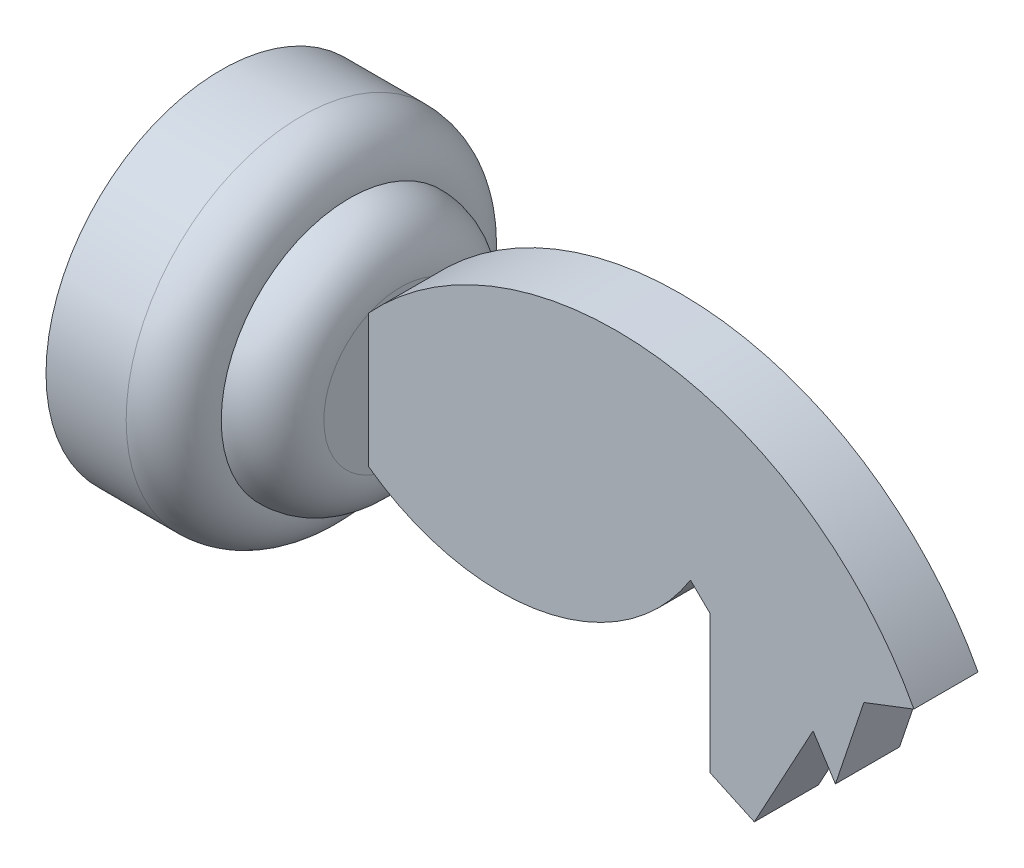
SolidWorks part; units mm, degrees
ref_plane "Спереди" through (0, 0, 0) normal (0, 0, 1) x (1, 0, 0)
ref_plane "Сверху" through (0, 0, 0) normal (0, 1, 0) x (1, 0, 0)
ref_plane "Справа" through (0, 0, 0) normal (1, 0, 0) x (0, 0, -1)
other "Configuration Table"
sketch "Эскиз1" plane through (0, 0, 0) normal (0, 0, 1) x (1, 0, 0)
  line L0 (0, 0) -> (71.2267, 0) construction
sketch "попа" plane through (0, 0, 0) normal (0, 0, 1) x (1, 0, 0)
  line L0 (0, 0) -> (0, 10.9299)
  line L1 (0, 10.9299) -> (5, 10.9299)
  line L3 (0, 0) -> (71.2267, 0) construction
  line L7 (11.2, 4.8) -> (11.2, 0)
  line L8 (11.2, 0) -> (0, 0)
  line L9 (8, 0) -> (8, 8)
  line L10 (11.2, 2.4) -> (11.2, 0)
  line L11 (0, 0) -> (-9.6864, 0) construction
  line L16 (1, 0) -> (3.5, 0)
  line L17 (1, 0) -> (1, 5.25)
  line L18 (1, 5.25) -> (3.5, 5.25)
  line L19 (3.5, 5.25) -> (3.5, 0)
  arc A0 (8, 8) -> (5, 10.9299) centre (5.0008, 7.9299) ccw
  arc A1 (11.2, 4.8) -> (8, 8) centre (8, 4.8) ccw
  dimension "D6" = 3
  dimension "D7" = 3.2
  dimension "D9" = 5.25
  dimension "D10" = 2.5
  dimension "D1" = 8
  dimension "D2" = 5
  dimension "D3" = 11.2
  dimension "D4" = 4.8
  dimension "D5" = 8
  dimension "D8" = 1
  dimension "D11" = 2.9992
revolve "Повернуть1" add sketch "попа" angle 360 about L0
sketch "вверх" plane through (0, 0, 0) normal (0, 0, 1) x (1, 0, 0)
  line L0 (11.2, 0) -> (11.2, 4.4)
  line L1 (11.2, -4.8) -> (11.2, 4.8) construction
  line L2 (11.2, 0) -> (45.2, 0)
  line L3 (0, 0) -> (71.2267, 0) construction
  line L5 (11.2, 0) -> (11.2, -3.915)
  line L6 (42.083, -1.2) -> (42.083, 0)
  line L7 (40.3075, -6.49) -> (40.3075, 0)
  line L8 (38.912, -4.32) -> (38.912, 0)
  line L9 (31.2635, 0) -> (32.499, -1.1973)
  line L10 (32.499, -1.1973) -> (32.499, -9.7973)
  line L11 (32.499, -9.7973) -> (35.2487, -11.07)
  line L12 (35.2487, -11.07) -> (38.912, -4.32)
  line L13 (38.912, -4.32) -> (40.3075, -6.49)
  line L14 (40.3075, -6.49) -> (42.083, -1.2)
  line L15 (42.083, -1.2) -> (45.2, 0)
  line L16 (35.2487, -11.07) -> (35.2487, 0)
  arc A1 (31.2635, 0) -> (11.2, -3.915) centre (19.3994, 7.4327) cw
  arc A2 (11.2, 4.4) -> (45.2, 0) centre (26.6431, -9.8306) cw
  dimension "D3" = 21
  dimension "D6" = 14
  dimension "D7" = 8.6
  dimension "D1" = 4.4
  dimension "D2" = 34
  dimension "D4" = 20.0635
  dimension "D5" = 3.915
  dimension "D8" = 1.7204
  dimension "D9" = 3.03
  dimension "D10" = 7.68
  dimension "D11" = 2.58
  dimension "D12" = 5.58
  dimension "D13" = 3.34
  dimension "D14" = 13.9365
  dimension "D15" = 1.2
  dimension "D16" = 6.49
  dimension "D17" = 4.32
  dimension "D18" = 11.07
extrude "верх" add sketch "вверх" along normal mid plane 4 contours A2 L0 L2 | A1 L2 L5 | L16 L12 L8 L2 | L11 L16 L2 L9 L10 | L7 L14 L6 L2 | L8 L13 L7 L2 | L6 L15 L2
